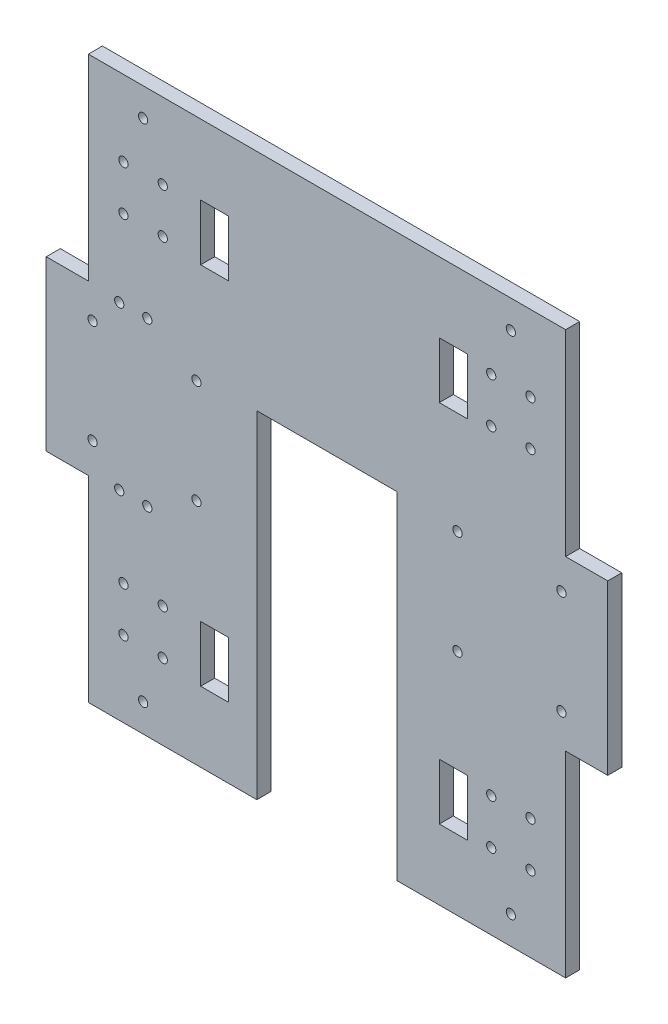
SolidWorks part; units mm, degrees
ref_plane "前视基准面" through (0, 0, 0) normal (0, 0, 1) x (1, 0, 0)
ref_plane "上视基准面" through (0, 0, 0) normal (0, 1, 0) x (1, 0, 0)
ref_plane "右视基准面" through (0, 0, 0) normal (1, 0, 0) x (0, 0, -1)
sketch "Model" plane through (0, 0, 0) normal (0, 0, 1) x (1, 0, 0)
  line L0 (202.7121, 317.514) -> (372.7121, 317.514)
  line L1 (372.7121, 117.514) -> (312.7121, 117.514)
  line L2 (312.7121, 117.514) -> (312.7121, 237.514)
  line L3 (312.7121, 237.514) -> (262.7121, 237.514)
  line L4 (262.7121, 237.514) -> (262.7121, 117.514)
  line L5 (262.7121, 117.514) -> (202.7121, 117.514)
  line L6 (187.7121, 187.514) -> (187.7121, 247.514)
  line L7 (252.7121, 142.514) -> (247.7121, 142.514)
  line L8 (252.7121, 142.514) -> (252.7121, 162.514)
  line L9 (252.7121, 162.514) -> (242.7121, 162.514)
  line L10 (242.7121, 162.514) -> (242.7121, 142.514)
  line L11 (242.7121, 142.514) -> (247.7121, 142.514)
  line L12 (327.7121, 142.514) -> (332.7121, 142.514)
  line L13 (327.7121, 142.514) -> (327.7121, 162.514)
  line L14 (327.7121, 162.514) -> (337.7121, 162.514)
  line L15 (337.7121, 162.514) -> (337.7121, 142.514)
  line L16 (337.7121, 142.514) -> (332.7121, 142.514)
  line L17 (252.7121, 292.514) -> (247.7121, 292.514)
  line L18 (252.7121, 292.514) -> (252.7121, 272.514)
  line L19 (252.7121, 272.514) -> (242.7121, 272.514)
  line L20 (242.7121, 272.514) -> (242.7121, 292.514)
  line L21 (242.7121, 292.514) -> (247.7121, 292.514)
  line L22 (327.7121, 292.514) -> (332.7121, 292.514)
  line L23 (327.7121, 292.514) -> (327.7121, 272.514)
  line L24 (327.7121, 272.514) -> (337.7121, 272.514)
  line L25 (337.7121, 272.514) -> (337.7121, 292.514)
  line L26 (337.7121, 292.514) -> (332.7121, 292.514)
  line L27 (202.7121, 317.514) -> (202.7121, 247.514)
  line L28 (202.7121, 247.514) -> (187.7121, 247.514)
  line L29 (202.7121, 117.514) -> (202.7121, 187.514)
  line L30 (202.7121, 187.514) -> (187.7121, 187.514)
  line L31 (372.7121, 317.514) -> (372.7121, 247.514)
  line L32 (372.7121, 247.514) -> (387.7121, 247.514)
  line L33 (372.7121, 117.514) -> (372.7121, 187.514)
  line L34 (372.7121, 187.514) -> (387.7121, 187.514)
  line L35 (387.7121, 247.514) -> (387.7121, 187.514)
  circle A0 centre (204.2121, 236.014) radius 1.65
  circle A1 centre (222.2121, 127.514) radius 1.65
  circle A2 centre (353.2121, 127.514) radius 1.65
  circle A3 centre (222.2121, 307.514) radius 1.65
  circle A4 centre (353.2121, 307.514) radius 1.65
  circle A5 centre (241.2121, 236.014) radius 1.65
  circle A6 centre (204.2121, 199.014) radius 1.65
  circle A7 centre (241.2121, 199.014) radius 1.65
  circle A8 centre (371.2121, 236.014) radius 1.65
  circle A9 centre (334.2121, 236.014) radius 1.65
  circle A10 centre (371.2121, 199.014) radius 1.65
  circle A11 centre (334.2121, 199.014) radius 1.65
  circle A12 centre (215.2121, 290.514) radius 1.65
  circle A13 centre (229.2121, 290.514) radius 1.65
  circle A14 centre (215.2121, 274.514) radius 1.65
  circle A15 centre (229.2121, 274.514) radius 1.65
  circle A16 centre (215.2121, 144.514) radius 1.65
  circle A17 centre (215.2121, 160.514) radius 1.65
  circle A18 centre (360.2121, 290.514) radius 1.65
  circle A19 centre (346.2121, 290.514) radius 1.65
  circle A20 centre (360.2121, 274.514) radius 1.65
  circle A21 centre (346.2121, 274.514) radius 1.65
  circle A22 centre (360.2121, 144.514) radius 1.65
  circle A23 centre (360.2121, 160.514) radius 1.65
  circle A24 centre (229.2121, 144.514) radius 1.65
  circle A25 centre (229.2121, 160.514) radius 1.65
  circle A26 centre (346.2121, 144.514) radius 1.65
  circle A27 centre (346.2121, 160.514) radius 1.65
  circle A28 centre (223.7121, 246.514) radius 1.65
  circle A29 centre (213.7121, 246.4422) radius 1.65
  circle A30 centre (223.7121, 188.514) radius 1.65
  circle A31 centre (213.7121, 188.5859) radius 1.65
extrude "凸台-拉伸1" add sketch "Model" along normal blind 5
